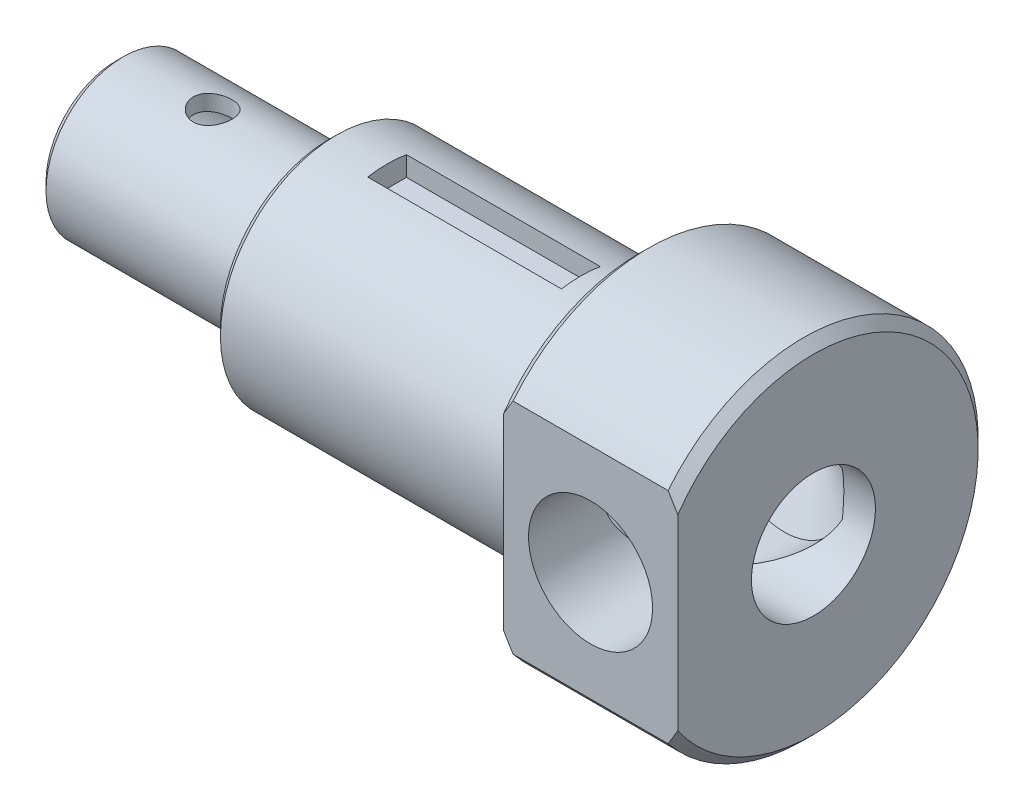
SolidWorks part; units mm, degrees
ref_plane "Спереди" through (0, 0, 0) normal (0, 0, 1) x (1, 0, 0)
ref_plane "Сверху" through (0, 0, 0) normal (0, 1, 0) x (1, 0, 0)
ref_plane "Справа" through (0, 0, 0) normal (1, 0, 0) x (0, 0, -1)
sketch "Эскиз1" plane through (0, 0, 0) normal (0, 0, 1) x (1, 0, 0)
  line L1 (0, 16) -> (0, 20)
  line L2 (0, 20) -> (55, 20)
  line L3 (55, 20) -> (55, 30)
  line L4 (55, 30) -> (135, 30)
  line L5 (135, 30) -> (135, 45)
  line L6 (135, 45) -> (180, 45)
  line L7 (180, 45) -> (180, 16)
  line L9 (0, 0) -> (-45.0163, 0) construction
  line L10 (0, 16) -> (180, 16)
  dimension "D1" = 60
  dimension "D2" = 40
  dimension "D3" = 90
  dimension "D4" = 180
  dimension "D5" = 55
  dimension "D6" = 80
  dimension "D7" = 32
revolve "Повернуть1" add sketch "Эскиз1" angle 360 about L9
sketch "Эскиз15" plane through (180, 0, 0) normal (1, 0, 0) x (0, 0, -1)
  line L0 (-35, 28.2843) -> (-35, -28.2843)
  circle A0 centre (0, 0) radius 45 construction
  circle M2 centre (0, 0) radius 45
  dimension "D1" = 80
extrude "Вырез-Вытянуть9" cut sketch "Эскиз15" against normal through all and the other way through all contours L0 M2
sketch "Эскиз6" plane through (0, 0, 0) normal (0, 0, 1) x (1, 0, 0)
  line L1 (70, 30) -> (120, 30)
  line L2 (70, 30) -> (70, 24.5)
  line L3 (70, 24.5) -> (120, 24.5)
  line L4 (120, 30) -> (120, 24.5)
  line L6 (135, 30) -> (55, 30) construction
  line L7 (55, 30) -> (55, -30) construction
  dimension "D1" = 50
  dimension "D2" = 15
  dimension "D3" = 5.5
extrude "Вырез-Вытянуть4" cut sketch "Эскиз6" against normal mid plane 10
sketch "Эскиз16" plane through (0, 0, 0) normal (0, 1, 0) x (1, 0, 0)
  line L0 (0, 0) -> (55, 0) construction
  line L1 (55, 20) -> (55, -20) construction
  circle A0 centre (25, 0) radius 5
  dimension "D1" = 10
  dimension "D2" = 25
extrude "Вырез-Вытянуть10" cut sketch "Эскиз16" against normal through all both and the other way through all
hole_wizard "Диаметр отверстия Ø0.15 (32)1" positions "Эскиз18" profile "Эскиз19" hole size "Ø0.15" standard "ISO"
sketch "Эскиз18" plane through (0, 0, 35) normal (0, 0, 1) x (1, 0, 0)
  line L0 (135, 0) -> (180, 0) construction
  line L1 (135, 30) -> (135, -30) construction
  line L2 (180, 28.2843) -> (180, -28.2843) construction
  point P0 (157.5, 0)
  point P12 (157.5, 0)
sketch "Эскиз19" plane through (157.5, 0, 35) normal (1, 0, 0) x (0, -1, 0)
  line L0 (0, 0) -> (0, 59.6138)
  line L1 (0, 59.6138) -> (16, 50)
  line L2 (16, 50) -> (16, 0)
  line L5 (16, 0) -> (0, 0)
  line L10 (0, 59.6138) -> (-16, 50) construction
  line L11 (0, -6.35) -> (0, 107.95) construction
  dimension "Диаметр отверстия" = 32
  dimension "Глубина отверстия" = 50
  dimension "Угол заточки сверла" = 118
chamfer "Фаска3" distance 2 angle 45 2 edges at (0, 0, -20) (55, 0, -30)
chamfer "Фаска4" distance 2.5 angle 45 2 edges at (135, 0, -45)
